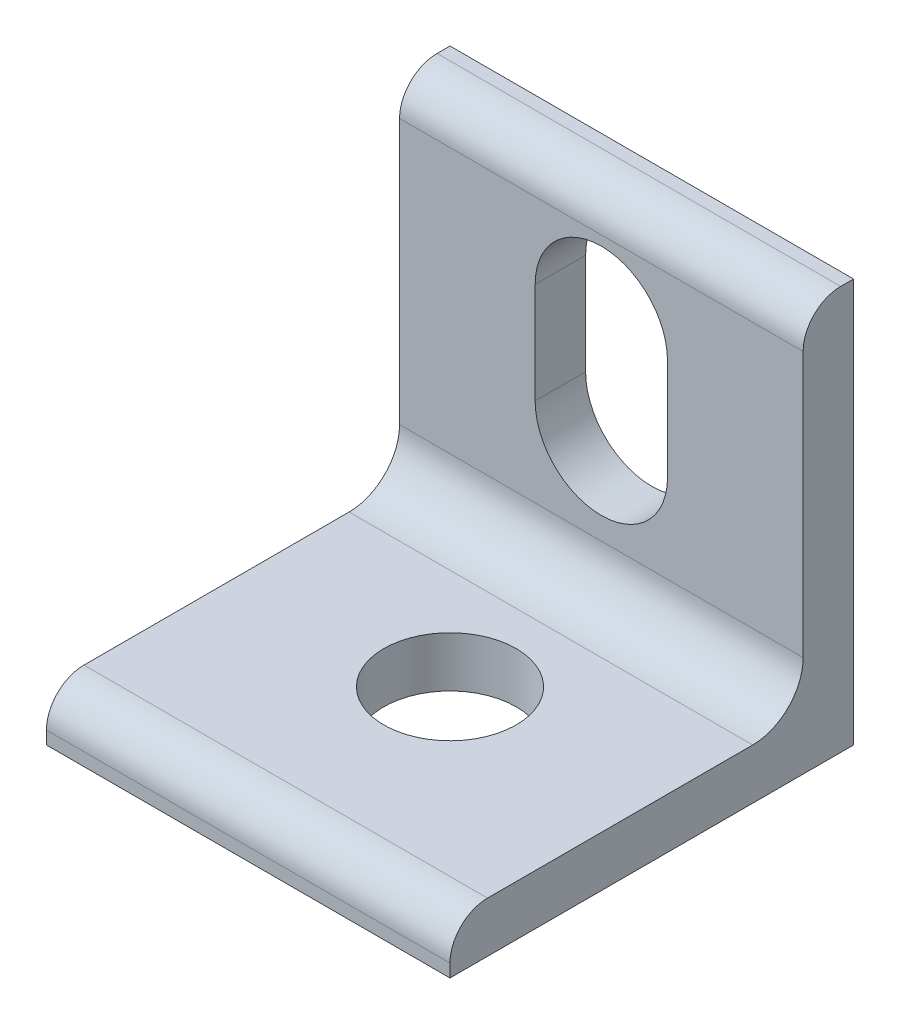
SolidWorks part; units mm, degrees
ref_plane "Front Plane" through (0, 0, 0) normal (0, 0, 1) x (1, 0, 0)
ref_plane "Top Plane" through (0, 0, 0) normal (0, 1, 0) x (1, 0, 0)
ref_plane "Right Plane" through (0, 0, 0) normal (1, 0, 0) x (0, 0, -1)
ref_plane "Plane1" through (12.7, 0, 0) normal (1, 0, 0) x (0, 0, -1)
sketch "Sketch1" plane through (12.7, 0, 0) normal (1, 0, 0) x (0, 0, -1)
  line L0 (0, 25.4) -> (-25.4, 25.4)
  line L1 (-25.4, 25.4) -> (-25.4, 0)
  line L2 (-25.4, 0) -> (0, 0)
  line L3 (0, 0) -> (0, 25.4)
extrude "Boss-Extrude1" add sketch "Sketch1" against normal blind 25.4
sketch "Sketch2" plane through (-12.7, 0, 0) normal (-1, 0, 0) x (0, 0, 1)
  line L0 (3.175, 3.175) -> (25.4, 3.175)
  line L1 (25.4, 3.175) -> (25.4, 25.4)
  line L2 (25.4, 25.4) -> (3.175, 25.4)
  line L3 (3.175, 25.4) -> (3.175, 3.175)
extrude "Cut-Extrude1" cut sketch "Sketch2" against normal through all
sketch "Sketch3" plane through (0, 0, 0) normal (0, 0, -1) x (-1, 0, 0)
  line L0 (-4.1656, 18.2626) -> (-4.1656, 11.9126)
  line L1 (4.1656, 11.9126) -> (4.1656, 18.2626)
  arc A0 (4.1656, 18.2626) -> (-4.1656, 18.2626) centre (0, 18.2626) ccw
  arc A1 (-4.1656, 11.9126) -> (4.1656, 11.9126) centre (0, 11.9126) ccw
extrude "Cut-Extrude2" cut sketch "Sketch3" against normal through all
hole_wizard "5/16 Clearance Hole1" positions "Sketch5" profile "Sketch4" hole size "5/16" standard "ANSI Inch"
sketch "Sketch5" plane through (0, 0, 0) normal (0, -1, 0) x (-1, 0, 0)
  point P0 (0, -12.7)
sketch "Sketch4" plane through (0, 0, 12.7) normal (1, 0, 0) x (0, 0, -1)
  line L0 (0, 0) -> (0, 25.4)
  line L1 (0, 25.4) -> (4.1656, 25.4)
  line L2 (4.1656, 25.4) -> (4.1656, 0)
  line L5 (4.1656, 0) -> (0, 0)
  line L11 (0, -6.35) -> (0, 107.95) construction
  dimension "Thru Hole Dia." = 8.3312
  dimension "Thru Hole Depth" = 25.4
fillet "Fillet1" radius 2.3622 2 edges at (0, 3.175, 25.4) (0, 25.4, 3.175)
fillet "Fillet2" radius 3.175 1 edges at (0, 3.175, 3.175)
